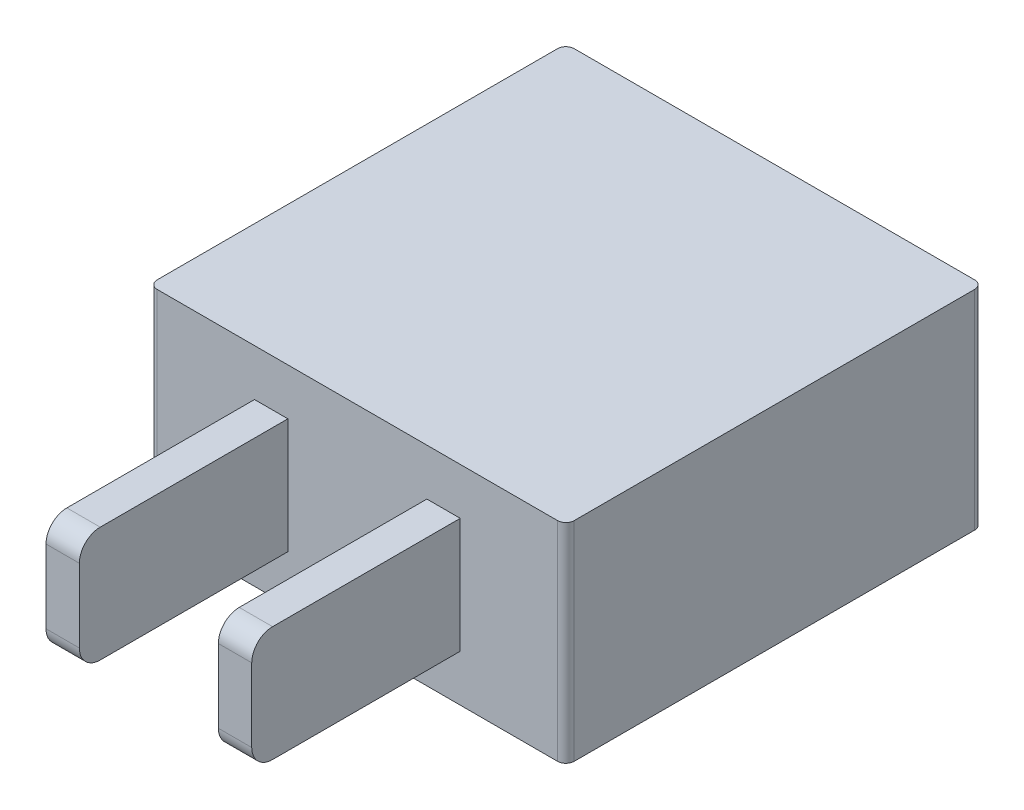
SolidWorks part; units mm, degrees
ref_plane "Front Plane" through (0, 0, 0) normal (0, 0, 1) x (1, 0, 0)
ref_plane "Top Plane" through (0, 0, 0) normal (0, 1, 0) x (1, 0, 0)
ref_plane "Right Plane" through (0, 0, 0) normal (1, 0, 0) x (0, 0, -1)
sketch "Sketch1" plane through (0, 0, 0) normal (0, 1, 0) x (1, 0, 0)
  line L1 (-6.35, -6.35) -> (6.35, -6.35)
  line L2 (-6.35, -6.35) -> (-6.35, 6.35)
  line L3 (-6.35, 6.35) -> (6.35, 6.35)
  line L4 (6.35, -6.35) -> (6.35, 6.35)
  line L5 (-6.35, -6.35) -> (6.35, 6.35) construction
  line L6 (-6.35, 6.35) -> (6.35, -6.35) construction
  point P0 (0, 0)
  dimension "D1" = 12.7
extrude "Boss-Extrude1" add sketch "Sketch1" along normal blind 6.35
sketch "Sketch2" plane through (0, 0, 6.35) normal (0, 0, 1) x (1, 0, 0)
  line L1 (-6.35, 6.35) -> (6.35, 6.35)
  line L2 (-6.35, 6.35) -> (-6.35, 0)
  line L3 (-6.35, 0) -> (6.35, 0)
  line L4 (6.35, 6.35) -> (6.35, 0)
  line L5 (-6.35, 6.35) -> (6.35, 0) construction
  line L6 (-6.35, 0) -> (6.35, 6.35) construction
  line L7 (-2.1167, 1.4224) -> (2.1167, 1.4224) construction
  line L8 (-2.1167, 1.4224) -> (-2.1167, 4.9276) construction
  line L9 (-2.1167, 4.9276) -> (2.1167, 4.9276) construction
  line L10 (2.1167, 1.4224) -> (2.1167, 4.9276) construction
  line L11 (-2.1167, 1.4224) -> (2.1167, 4.9276) construction
  line L12 (-2.1167, 4.9276) -> (2.1167, 1.4224) construction
  line L13 (2.1167, 4.9276) -> (3.1327, 4.9276)
  line L14 (2.1167, 4.9276) -> (2.1167, 1.4224)
  line L15 (2.1167, 1.4224) -> (3.1327, 1.4224)
  line L16 (3.1327, 4.9276) -> (3.1327, 1.4224)
  line L17 (2.1167, 4.9276) -> (3.1327, 1.4224) construction
  line L18 (2.1167, 1.4224) -> (3.1327, 4.9276) construction
  line L19 (-2.1167, 1.4224) -> (-3.1327, 1.4224)
  line L20 (-2.1167, 1.4224) -> (-2.1167, 4.9276)
  line L21 (-2.1167, 4.9276) -> (-3.1327, 4.9276)
  line L22 (-3.1327, 1.4224) -> (-3.1327, 4.9276)
  line L23 (-2.1167, 1.4224) -> (-3.1327, 4.9276) construction
  line L24 (-2.1167, 4.9276) -> (-3.1327, 1.4224) construction
  point P4 (0, 3.175)
  point P7 (0, 3.175)
  point P14 (2.6247, 3.175)
  point P17 (-2.6247, 3.175)
  dimension "D1" = 4.2333
  dimension "D2" = 3.5052
  dimension "D3" = 1.016
extrude "Boss-Extrude2" add sketch "Sketch2" along normal blind 6.35 contours L22 L19 L20 L21 | L16 L13 L14 L15
fillet "Fillet1" radius 0.635 4 edges at (2.6247, 4.9276, 12.7) (2.6247, 1.4224, 12.7) (-2.6247, 1.4224, 12.7) (-2.6247, 4.9276, 12.7)
fillet "Fillet2" radius 0.254 4 edges at (-6.35, 3.175, -6.35) (6.35, 3.175, -6.35) (6.35, 3.175, 6.35) (-6.35, 3.175, 6.35)
